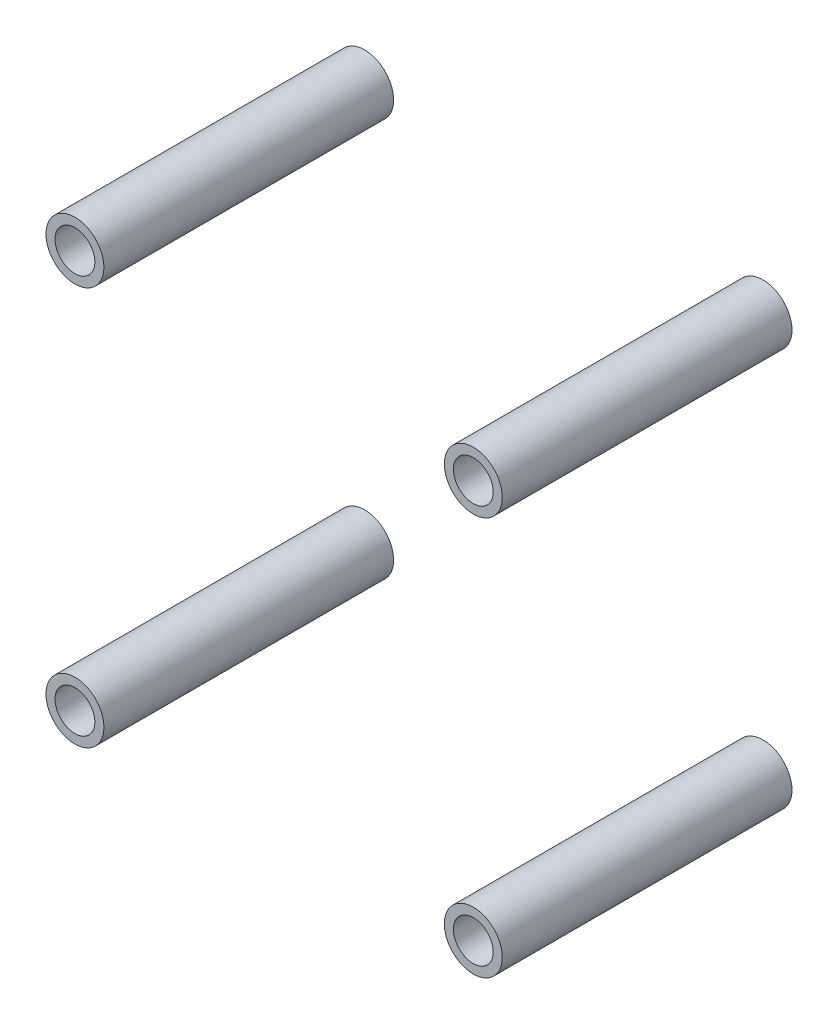
SolidWorks part; units mm, degrees
material "PBT General Purpose"
ref_plane "Front Plane" through (0, 0, 0) normal (0, 0, 1) x (1, 0, 0)
ref_plane "Top Plane" through (0, 0, 0) normal (0, 1, 0) x (1, 0, 0)
ref_plane "Right Plane" through (0, 0, 0) normal (1, 0, 0) x (0, 0, -1)
sketch "Sketch1" plane through (0, 0, 111.125) normal (0, 0, 1) x (1, 0, 0)
  circle A0 centre (27.5, 251.9) radius 2.75 construction
  circle A1 centre (-27.5, 251.9) radius 2.75 construction
  circle A2 centre (-27.5, 306.9) radius 2.75 construction
  circle A3 centre (27.5, 306.9) radius 2.75 construction
  circle A4 centre (27.5, 251.9) radius 2.75
  circle A5 centre (-27.5, 251.9) radius 2.75
  circle A6 centre (-27.5, 306.9) radius 2.75
  circle A7 centre (27.5, 306.9) radius 2.75
  circle A8 centre (27.5, 306.9) radius 4
  circle A9 centre (-27.5, 306.9) radius 4
  circle A10 centre (-27.5, 251.9) radius 4
  circle A11 centre (27.5, 251.9) radius 4
  dimension "D1" = 8
extrude "Boss-Extrude1" add sketch "Sketch1" along normal blind 40
